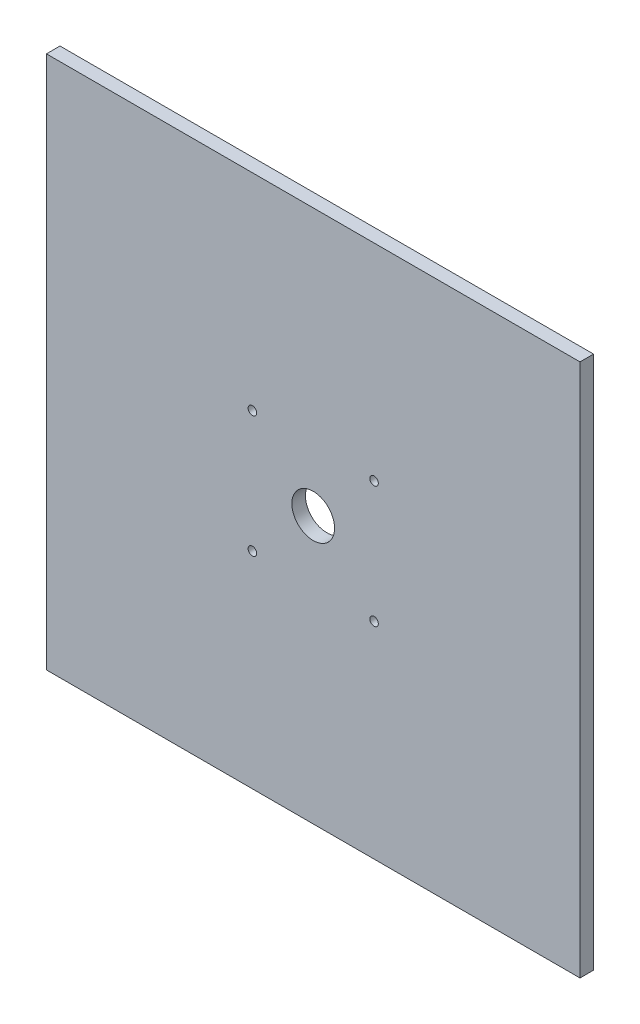
SolidWorks part; units mm, degrees
ref_plane "Alzado" through (0, 0, 0) normal (0, 0, 1) x (1, 0, 0)
ref_plane "Planta" through (0, 0, 0) normal (0, 1, 0) x (1, 0, 0)
ref_plane "Vista lateral" through (0, 0, 0) normal (1, 0, 0) x (0, 0, -1)
sketch "Sketch1" plane through (0, 0, 0) normal (0, 0, 1) x (1, 0, 0)
  line L1 (250, -250) -> (-250, -250)
  line L2 (250, -250) -> (250, 250)
  line L3 (250, 250) -> (-250, 250)
  line L4 (-250, -250) -> (-250, 250)
  line L5 (250, -250) -> (-250, 250) construction
  line L6 (250, 250) -> (-250, -250) construction
  point P0 (0, 0)
  dimension "D1" = 500
extrude "Boss-Extrude1" add sketch "Sketch1" along normal blind 12.7
sketch "Sketch4" plane through (0, 0, 12.7) normal (0, 0, 1) x (1, 0, 0)
  circle A0 centre (0, 0) radius 20
  dimension "D1" = 40
extrude "Cut-Extrude1" cut sketch "Sketch4" against normal up to surface (12.7 mm away) up to face at (0, 0, 0)
hole_wizard "Ø8.0 mm Dowel Holes1" positions "Sketch5" profile "Sketch6" hole size "Ø8.0" standard "ANSI Metric"
sketch "Sketch5" plane through (0, 0, 0) normal (0, 0, -1) x (-1, 0, 0)
  point P0 (57, 57)
  point P2 (-57, 57)
  point P4 (-57, -57)
  point P6 (57, -57)
  point P10 (0, 0)
  point P11 (0, 0)
  point P12 (0, 0)
  dimension "D1" = 114
  dimension "D2" = 114
  dimension "D3" = 57
  dimension "D4" = 57
sketch "Sketch6" plane through (-57, 57, 0) normal (1, 0, 0) x (0, 1, 0)
  line L0 (0, 0) -> (0, 22.1534)
  line L1 (0, 22.1534) -> (4, 19.75)
  line L2 (4, 19.75) -> (4, 0)
  line L5 (4, 0) -> (0, 0)
  line L10 (0, 22.1534) -> (-4, 19.75) construction
  line L11 (0, -6.35) -> (0, 107.95) construction
  dimension "Hole Dia." = 8
  dimension "Hole Depth" = 19.75
  dimension "Drill Angle" = 118
